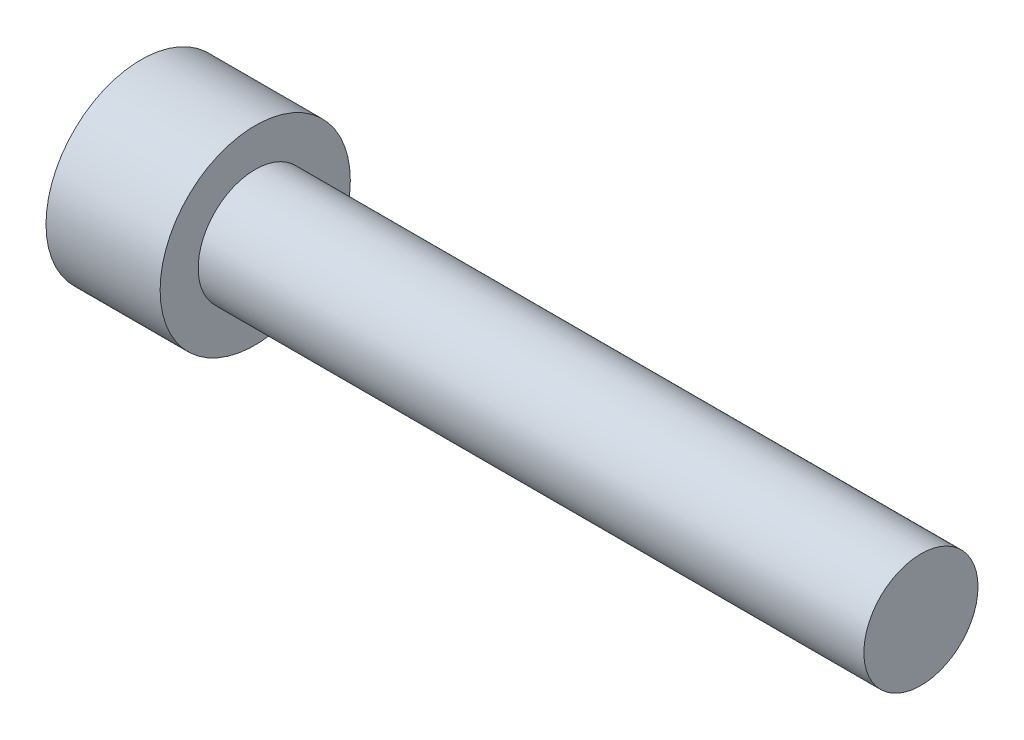
SolidWorks part; units mm, degrees
ref_plane "前视基准面" through (0, 0, 0) normal (0, 0, 1) x (1, 0, 0)
ref_plane "上视基准面" through (0, 0, 0) normal (0, 1, 0) x (1, 0, 0)
ref_plane "右视基准面" through (0, 0, 0) normal (1, 0, 0) x (0, 0, -1)
sketch "草图1" plane through (0, 0, 0) normal (1, 0, 0) x (0, 0, -1)
  circle A0 centre (0, 0) radius 5
extrude "凸台-拉伸1" add sketch "草图1" along normal blind 6
sketch "草图2" plane through (0, 0, 0) normal (-1, 0, 0) x (0, 0, 1)
  line L0 (-2.1651, 1.25) -> (0, 2.5)
  line L1 (0, 2.5) -> (2.1651, 1.25)
  line L2 (2.1651, 1.25) -> (2.1651, -1.25)
  line L3 (2.1651, -1.25) -> (0, -2.5)
  line L4 (0, -2.5) -> (-2.1651, -1.25)
  line L5 (-2.1651, -1.25) -> (-2.1651, 1.25)
  point P17 (0, 0)
  dimension "D1" = 6
extrude "切除-拉伸1" cut sketch "草图2" against normal blind 3
sketch "草图3" plane through (6, 0, 0) normal (1, 0, 0) x (0, 0, -1)
  circle A0 centre (0, 0) radius 3
extrude "凸台-拉伸2" add sketch "草图3" along normal blind 35
